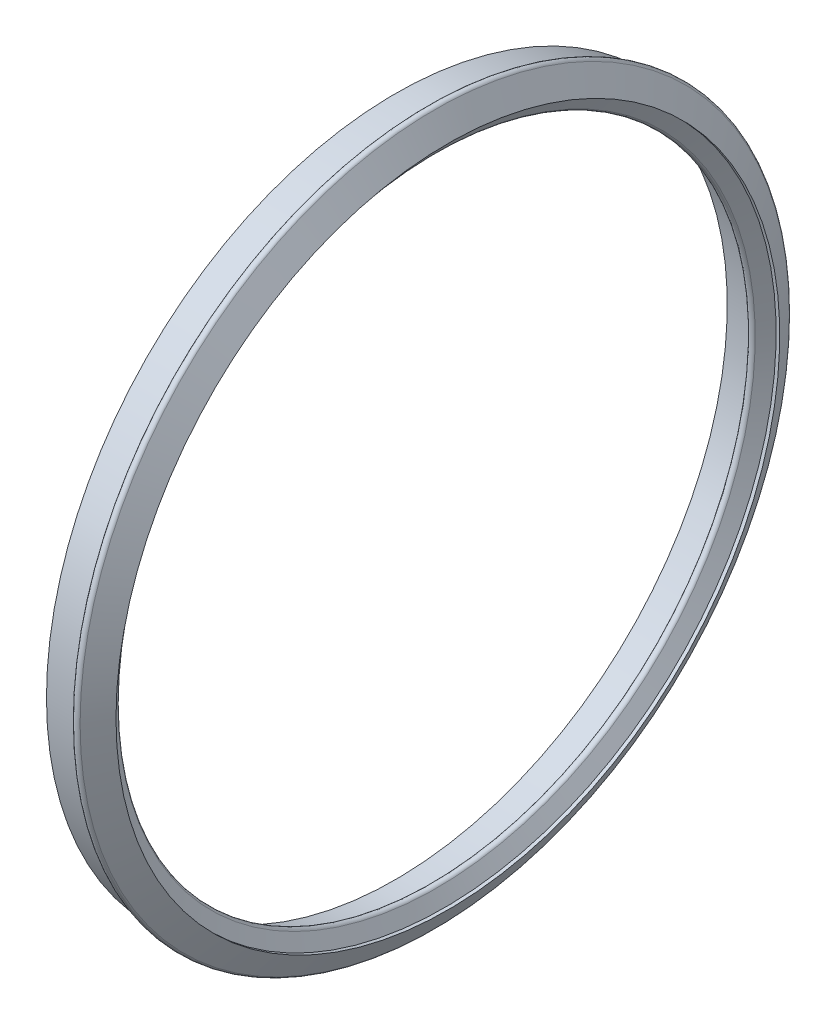
SolidWorks part; units mm, degrees
material "Эпоксидный клей без наполнителя"
ref_plane "Спереди" through (0, 0, 0) normal (0, 0, 1) x (1, 0, 0)
ref_plane "Сверху" through (0, 0, 0) normal (0, 1, 0) x (1, 0, 0)
ref_plane "Справа" through (0, 0, 0) normal (1, 0, 0) x (0, 0, -1)
sketch "Эскиз1" plane through (0, 0, 0) normal (0, 0, 1) x (1, 0, 0)
  line L0 (0, 18.4) -> (1.5536, 18.4)
  line L1 (1.5536, 18.4) -> (1.7268, 18.7)
  line L2 (0, 17.5) -> (1.4226, 17.5)
  line L3 (1.4226, 17.5) -> (1.8268, 16.8)
  line L4 (2.1732, 16.8) -> (2.5774, 17.5)
  line L5 (2.0732, 18.7) -> (2.766, 17.5)
  line L6 (2.5774, 17.5) -> (2.766, 17.5)
  line L7 (0, 18.4) -> (0, 17.5)
  line L8 (0, 0) -> (22.375, 0) construction
  arc A0 (1.8268, 16.8) -> (2.1732, 16.8) centre (2, 16.9) ccw
  arc A1 (2.0732, 18.7) -> (1.7268, 18.7) centre (1.9, 18.6) ccw
  point P12 (2, 16.5)
  point P17 (1.9, 19)
  dimension "D10" = 0.2
  dimension "D1" = 1
  dimension "D2" = 60
  dimension "D3" = 60
  dimension "D4" = 2
  dimension "D5" = 1.9
  dimension "D6" = 30
  dimension "D7" = 30
  dimension "D8" = 17.5
  dimension "D9" = 0.9
revolve "Повернуть1" add sketch "Эскиз1" angle 360 about L8
